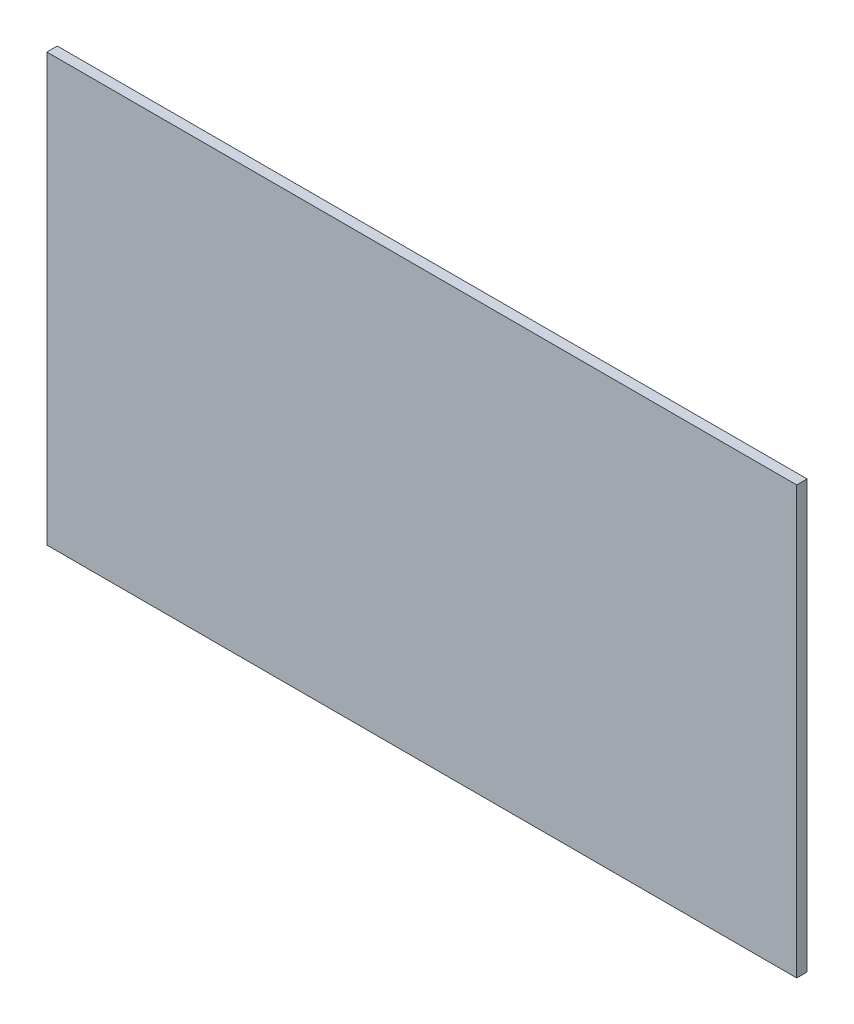
SolidWorks part; units mm, degrees
ref_plane "Front Plane" through (0, 0, 0) normal (0, 0, 1) x (1, 0, 0)
ref_plane "Top Plane" through (0, 0, 0) normal (0, 1, 0) x (1, 0, 0)
ref_plane "Right Plane" through (0, 0, 0) normal (1, 0, 0) x (0, 0, -1)
sketch "Sketch1" plane through (0, 0, 0) normal (0, 0, 1) x (1, 0, 0)
  line L1 (914.4, 520.7) -> (-914.4, 520.7)
  line L2 (914.4, 520.7) -> (914.4, -520.7)
  line L3 (914.4, -520.7) -> (-914.4, -520.7)
  line L4 (-914.4, 520.7) -> (-914.4, -520.7)
  line L5 (914.4, 520.7) -> (-914.4, -520.7) construction
  line L6 (914.4, -520.7) -> (-914.4, 520.7) construction
  point P0 (0, 0)
  dimension "D1" = 1828.8
  dimension "D2" = 1041.4
extrude "Boss-Extrude1" add sketch "Sketch1" along normal blind 25.4
